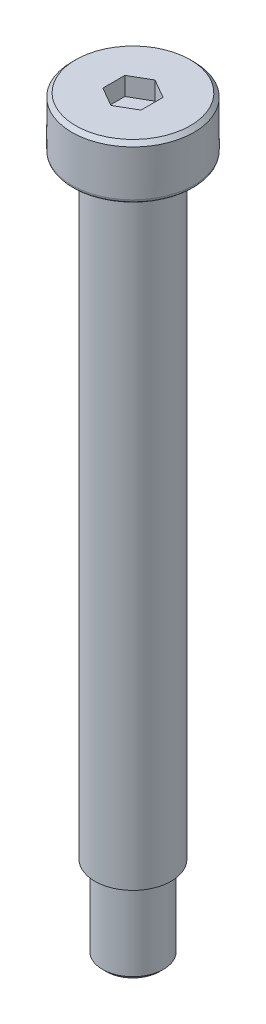
SolidWorks part; units mm, degrees
material "Plain Carbon Steel"
ref_plane "Front Plane" through (0, 0, 0) normal (0, 0, 1) x (1, 0, 0)
ref_plane "Top Plane" through (0, 0, 0) normal (0, 1, 0) x (1, 0, 0)
ref_plane "Right Plane" through (0, 0, 0) normal (1, 0, 0) x (0, 0, -1)
sketch "Sketch1" plane through (0, 0, 0) normal (0, 0, 1) x (1, 0, 0)
  line L0 (0, 0) -> (8, 0)
  line L1 (8, 0) -> (8, -7)
  line L2 (8, -7) -> (4.75, -7)
  line L3 (4.75, -7) -> (4.75, -7.5)
  line L4 (4.75, -7.5) -> (5, -7.5)
  line L5 (5, -7.5) -> (5, -87)
  line L6 (5, -87) -> (4, -87)
  line L7 (4, -87) -> (4, -98)
  line L8 (4, -98) -> (0, -98)
  line L9 (0, -98) -> (0, 0)
  line L10 (0, 5) -> (0, -103) construction
  dimension "D1" = 5
  dimension "D2" = 5
  dimension "D3" = 8
  dimension "D4" = 10
  dimension "D5" = 0.25
  dimension "D6" = 16
  dimension "Length" = 80
  dimension "D8" = 7
  dimension "D9" = 0.5
  dimension "D10" = 11
revolve "Revolve1" add sketch "Sketch1" angle 360 about L10
sketch "Sketch2" plane through (0, 0, 0) normal (0, 1, 0) x (1, 0, 0)
  line L1 (0, -2.8868) -> (2.5, -1.4434)
  line L2 (2.5, -1.4434) -> (2.5, 1.4434)
  line L3 (2.5, 1.4434) -> (0, 2.8868)
  line L4 (0, 2.8868) -> (-2.5, 1.4434)
  line L5 (-2.5, 1.4434) -> (-2.5, -1.4434)
  line L6 (-2.5, -1.4434) -> (0, -2.8868)
  circle A0 centre (0, 0) radius 2.5 construction
  dimension "D1" = 5
extrude "Cut-Extrude1" cut sketch "Sketch2" against normal blind 2.4
chamfer "Chamfer1" distance 0.5 angle 45 1 edges at (-8, 0, 0)
fillet "Fillet1" radius 0.5 1 edges at (-8, -7, 0)
chamfer "Chamfer2" distance 0.5 angle 45 1 edges at (-4, -98, 0)
